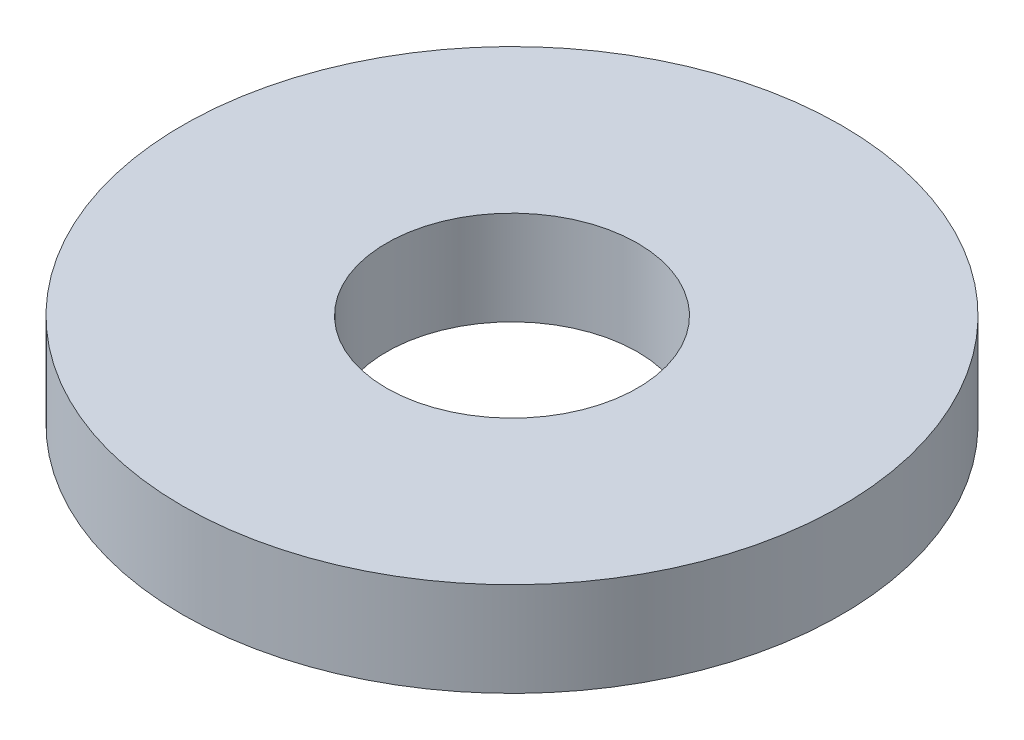
SolidWorks part; units mm, degrees
ref_plane "Front Plane" through (0, 0, 0) normal (0, 0, 1) x (1, 0, 0)
ref_plane "Top Plane" through (0, 0, 0) normal (0, 1, 0) x (1, 0, 0)
ref_plane "Right Plane" through (0, 0, 0) normal (1, 0, 0) x (0, 0, -1)
sketch "Sketch1" plane through (0, 0, 0) normal (0, 1, 0) x (1, 0, 0)
  circle A0 centre (0, 0) radius 42
  circle A1 centre (0, 0) radius 16
  dimension "D1" = 32
  dimension "D2" = 84
extrude "Boss-Extrude1" add sketch "Sketch1" along normal mid plane 12
